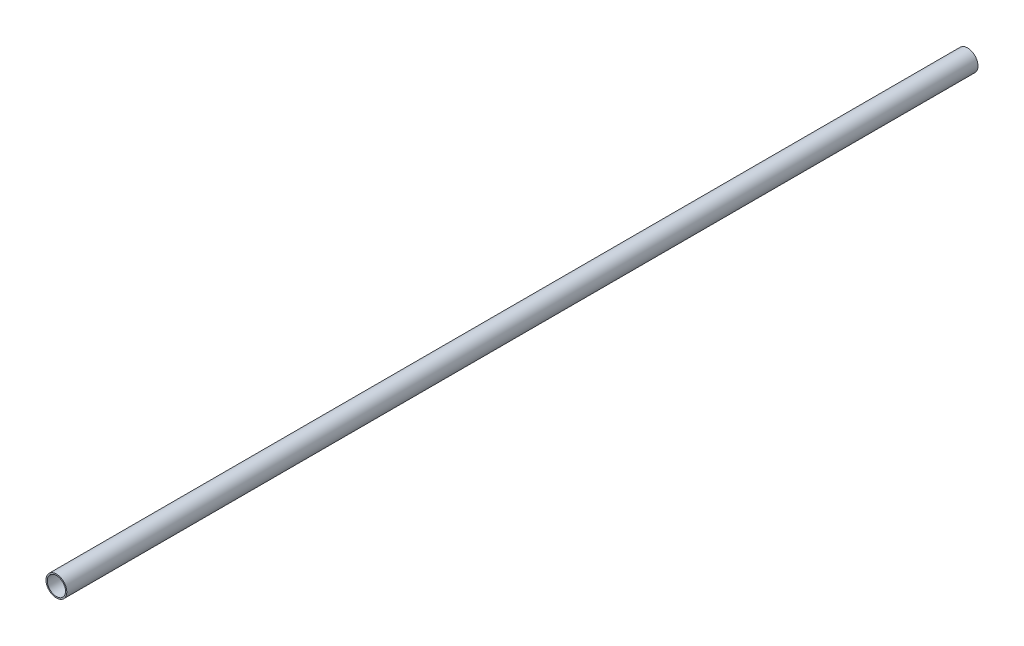
SolidWorks part; units mm, degrees
material "Poltrusion Carbon Fiber"
ref_plane "Front Plane" through (0, 0, 0) normal (0, 0, 1) x (1, 0, 0)
ref_plane "Top Plane" through (0, 0, 0) normal (0, 1, 0) x (1, 0, 0)
ref_plane "Right Plane" through (0, 0, 0) normal (1, 0, 0) x (0, 0, -1)
sketch "Эскиз1" plane through (0, 0, 0) normal (0, 0, 1) x (1, 0, 0)
  circle A0 centre (0, 0) radius 8
  circle A1 centre (0, 0) radius 7
  dimension "D1" = 16
  dimension "D2" = 1
extrude "Бобышка-Вытянуть1" add sketch "Эскиз1" along normal mid plane 700
equation "\"DTailTube\"= 16мм'Диаметр трубки хвостового оперения"
equation "\"FusLenght\"= 700мм"
equation "\"DMotor\"= 35.2мм"
equation "\"MotorArm\"= 225мм"
equation "\"DFus\"= 130мм"
equation "\"DFusTube\"= 16мм'Диаметр трубки внутри фюзеляжа"
equation "\"FusTubeHeight\"= 30мм"
equation "\"FusCentralPartLenght\"= 350мм"
equation "\"FusNoseLenght\"= 170мм"
equation "\"WingOffset\"= 1мм'Расстояние от внутренней поверхности фюзеляжа до профиля крыла по вертикали"
equation "\"EllipseRatio\"= 1.1'Центральная часть фюзеляжа - эллипс. Этот параметр - отношение длин осей эллипса"
equation "\"FrameOffset\"= 0.6мм"
equation "\"DThreadedInsert\"= 3.6мм'Внешний диамер резьбовых втулок"
equation "\"CenterSectionLenght\"= 140мм'Длина центроплана"
equation "\"b\"= 1680мм'Размах"
equation "\"cwr\"= 236мм'Корневая хорда крыла"
equation "\"TR\"= 0.75'Сужение крыла"
equation "\"cwt\"= \"TR\" * \"cwr\"'Концевая хорда крыла"
equation "\"DWingMainSpar\"= 16мм'Диаметр главного лонжерона крыла"
equation "\"DWingSecondSpar\"= 8мм'Диаметр второго лонжерона крыла"
equation "\"WingSparsDistance\"= 80мм'Расстояния между отверстиями по лонжерон крыла"
equation "\"c\"= 210мм'САХ крыла"
equation "\"D1@Эскиз1\"=\"DFusTube\""
equation "\"D1@Бобышка-Вытянуть1\"=\"FusLenght\""
